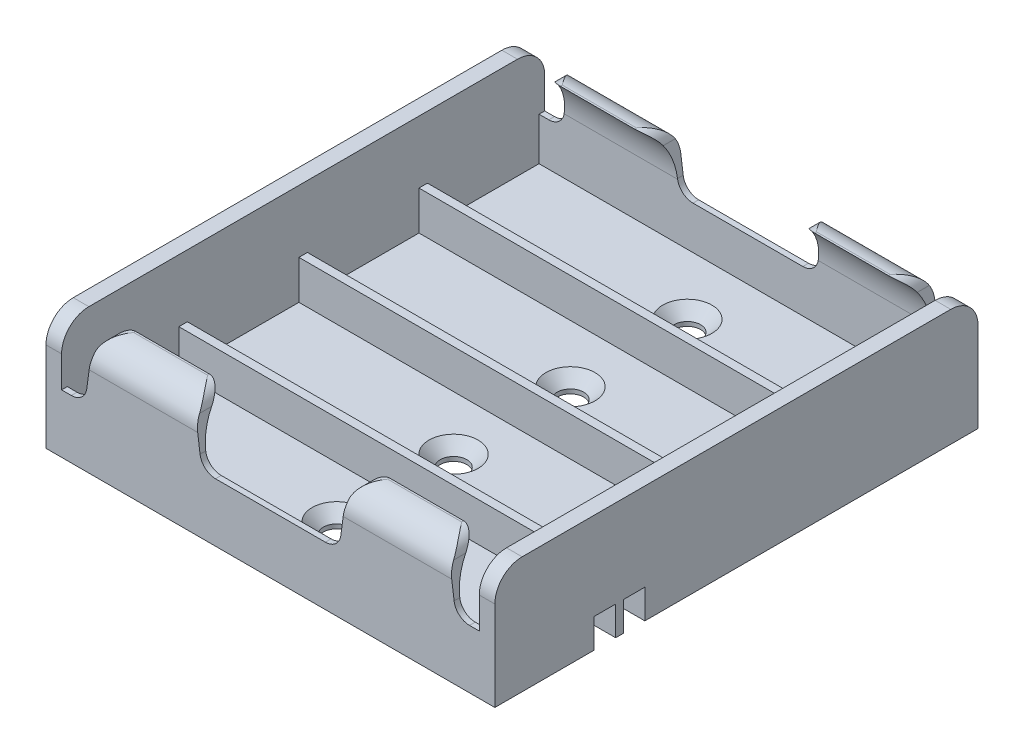
SolidWorks part; units mm, degrees
ref_plane "Front Plane" through (0, 0, 0) normal (0, 0, 1) x (1, 0, 0)
ref_plane "Top Plane" through (0, 0, 0) normal (0, 1, 0) x (1, 0, 0)
ref_plane "Right Plane" through (0, 0, 0) normal (1, 0, 0) x (0, 0, -1)
sketch "Sketch1" plane through (0, 0, 0) normal (1, 0, 0) x (0, 0, -1)
  line L0 (0, 0) -> (31, 0)
  line L1 (31, 0) -> (31, 11.5)
  line L2 (27.5, 15) -> (0, 15)
  line L3 (0, 15) -> (0, 0)
  line L4 (-31, 0) -> (0, 0) construction
  arc A0 (31, 11.5) -> (27.5, 15) centre (27.5, 11.5) ccw
  dimension "D3" = 3.5
  dimension "D1" = 15
  dimension "D2" = 62
extrude "Boss-Extrude1" add sketch "Sketch1" along normal mid plane 57.6
mirror "Mirror1" about plane through (28.8, 15, 0) normal (0, 0, -1) of "Boss-Extrude1"
sketch "Sketch2" plane through (28.8, 0, 0) normal (1, 0, 0) x (0, 0, -1)
  line L0 (-31, 0) -> (31, 0) construction
  line L1 (-18.25, 0) -> (-15.5, 0)
  line L2 (-18.25, 0) -> (-18.25, 3.75)
  line L3 (-18.25, 3.75) -> (-15.5, 3.75)
  line L4 (-15.5, 0) -> (-15.5, 3.75)
  line L5 (-31, 0) -> (-31, 11.5) construction
  line L6 (-14.5, 0) -> (-11.75, 0)
  line L7 (-14.5, 0) -> (-14.5, 3.75)
  line L8 (-14.5, 3.75) -> (-11.75, 3.75)
  line L9 (-11.75, 0) -> (-11.75, 3.75)
  dimension "D1" = 12.75
  dimension "D2" = 1
  dimension "D3" = 3.75
  dimension "D4" = 2.75
extrude "Cut-Extrude1" cut sketch "Sketch2" against normal blind 3.75
sketch "Sketch3" plane through (28.8, 0, 0) normal (1, 0, 0) x (0, 0, -1)
  line L0 (-30.27, 9.16) -> (-30.27, 2)
  line L1 (-30.27, 2) -> (-15.95, 2)
  line L2 (-15.95, 2) -> (-15.95, 9.16)
  line L3 (-31, 0) -> (-18.25, 0) construction
  line L4 (-31, 0) -> (-15.5, 0) construction
  line L5 (-15.5, 0) -> (0, 0) construction
  line L6 (-23.25, 0) -> (-23.11, 2) construction
  line L7 (-14.8633, 9.16) -> (-14.8633, 2)
  line L8 (-14.8633, 2) -> (-0.5433, 2)
  line L9 (-0.5433, 2) -> (-0.5433, 9.16)
  line L10 (-15.95, 2) -> (-15.4067, 2) construction
  line L11 (-15.4067, 2) -> (-14.8633, 2) construction
  line L12 (-0.5433, 2) -> (0, 2) construction
  line L13 (0, 2) -> (0, 0) construction
  arc A0 (-15.95, 9.16) -> (-30.27, 9.16) centre (-23.11, 9.16) ccw
  arc A1 (-30.27, 9.16) -> (-23.11, 2) centre (-23.11, 9.16) ccw construction
  arc A2 (-23.11, 2) -> (-15.95, 9.16) centre (-23.11, 9.16) ccw construction
  arc A3 (-14.8633, 9.16) -> (-0.5433, 9.16) centre (-7.7033, 9.16) cw
  dimension "D1" = 0.45
  dimension "D3" = 14.32
  dimension "D2" = 2
extrude "Cut-Extrude2" cut sketch "Sketch3" against normal offset from surface (53.6 mm away) 2 from offset 2 offset against normal yes
mirror "Mirror2" about plane through (0, 0, 0) normal (0, 0, 1) of "Cut-Extrude2"
sketch "Sketch4" plane through (0, 15, 0) normal (0, 1, 0) x (1, 0, 0)
  line L1 (-26.8, 27.2525) -> (26.8, 27.2525)
  line L2 (-26.8, 27.2525) -> (-26.8, -27.2525)
  line L3 (-26.8, -27.2525) -> (26.8, -27.2525)
  line L4 (26.8, 27.2525) -> (26.8, -27.2525)
extrude "Cut-Extrude3" cut sketch "Sketch4" against normal offset from surface (8 mm away) 5 up to face at (0, 2, -7.7033)
sketch "Sketch5" plane through (0, 2, 0) normal (0, 1, 0) x (1, 0, 0)
  line L0 (0, 22.5) -> (0, 7.5) construction
  line L1 (0, 7.5) -> (0, -7.5) construction
  line L2 (0, -7.5) -> (0, -22.5) construction
  point P2 (0, 0)
  point P5 (0, 22.5)
  point P7 (0, 0)
  point P8 (0, 7.5)
  point P9 (0, -7.5)
  point P10 (0, -22.5)
  dimension "D1" = 15
hole_wizard "CSK for M3 Flat Head Machine Screw1" positions "3DSketch1" profile "Sketch6" countersink size "M3" standard "ANSI Metric"
sketch3d "3DSketch1"
  point P0 (0, 2, -22.5)
  point P3 (0, 2, -7.5)
  point P6 (0, 2, 7.5)
  point P9 (0, 2, 22.5)
sketch "Sketch6" plane through (0, 2, -22.5) normal (1, 0, 0) x (0, 0, 1)
  line L0 (0, 0) -> (0, 8.8955)
  line L1 (0, 8.8955) -> (1.7, 7.874)
  line L2 (1.7, 7.874) -> (1.7, 1.45)
  line L3 (1.7, 1.45) -> (3.15, 0)
  line L5 (3.15, 0) -> (0, 0)
  line L6 (-1.7, 1.45) -> (-3.15, 0) construction
  line L10 (0, 8.8955) -> (-1.7, 7.874) construction
  line L11 (0, -6.35) -> (0, 107.95) construction
  dimension "Hole Dia." = 3.4
  dimension "Hole Depth" = 7.874
  dimension "Near C'Sink Dia." = 6.3
  dimension "Near C'Sink Angle" = 90
  dimension "Drill Angle" = 118
sketch "Sketch7" plane through (0, 0, 0) normal (0, 0, 1) x (1, 0, 0)
  line L0 (-26.8, 15) -> (-26.8, 7.5)
  line L1 (-9.5686, 13.2643) -> (-9.0314, 9.2357)
  line L2 (-26.8, 7.5) -> (-25.551, 7.5)
  line L3 (-23.8, 7.5) -> (-22.8, 15) construction
  line L4 (28.8, 15) -> (-28.8, 15) construction
  line L5 (-22.8, 15) -> (-26.8, 15)
  line L6 (-9.8, 15) -> (-8.8, 7.5) construction
  line L7 (-7.049, 7.5) -> (0, 7.5)
  line L9 (0, 15) -> (-9.8, 15)
  line L10 (28.8, 0) -> (-28.8, 0) construction
  line L13 (-23.0314, 13.2643) -> (-23.5686, 9.2357)
  line L16 (-22.8, 15) -> (-21.049, 15)
  line L18 (-11.551, 15) -> (-9.8, 15)
  line L19 (-25.551, 7.5) -> (-23.8, 7.5) construction
  line L20 (-8.8, 7.5) -> (-7.049, 7.5) construction
  line L21 (0, 15) -> (0, 7.5)
  arc A0 (-23.0314, 13.2643) -> (-21.049, 15) centre (-21.049, 13) cw
  arc A1 (-23.5686, 9.2357) -> (-25.551, 7.5) centre (-25.551, 9.5) cw
  arc A2 (-11.551, 15) -> (-9.5686, 13.2643) centre (-11.551, 13) cw
  arc A3 (-9.0314, 9.2357) -> (-7.049, 7.5) centre (-7.049, 9.5) ccw
  dimension "D5" = 2
  dimension "D1" = 7.5
  dimension "D2" = 3
  dimension "D3" = 4
  dimension "D4" = 15
extrude "Cut-Extrude4" cut sketch "Sketch7" against normal through all both and the other way through all
mirror "Mirror3" about plane through (0, 0, 0) normal (1, 0, 0) of "Cut-Extrude4"
